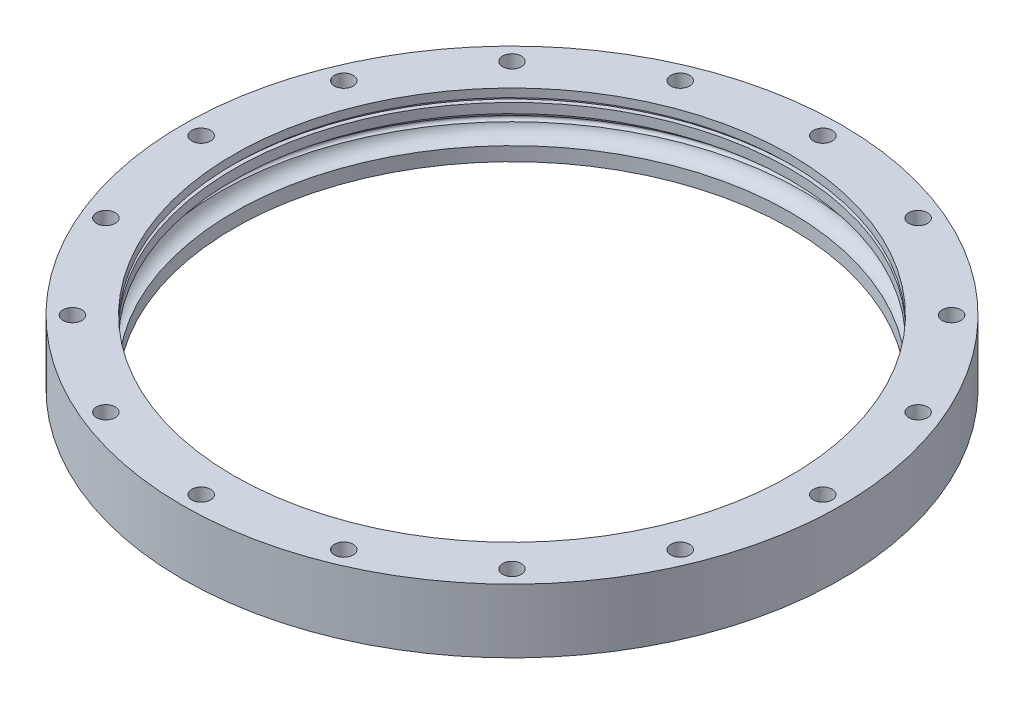
SolidWorks part; units mm, degrees
ref_plane "Plan de face" through (0, 0, 0) normal (0, 0, 1) x (1, 0, 0)
ref_plane "Plan de dessus" through (0, 0, 0) normal (0, 1, 0) x (1, 0, 0)
ref_plane "Plan de droite" through (0, 0, 0) normal (1, 0, 0) x (0, 0, -1)
sketch "Esquisse1" plane through (0, 0, 0) normal (0, 0, 1) x (1, 0, 0)
  line L0 (0, 0) -> (-237.5, 0) construction
  line L1 (-237.5, 0) -> (-237.5, 46)
  line L2 (-237.5, 46) -> (0, 46) construction
  line L3 (0, 46) -> (0, 0) construction
  line L4 (-237.5, 0) -> (-200.5, 0)
  line L5 (-200.5, 0) -> (-200.5, 10)
  line L6 (-200.5, 10) -> (-200.5, 30) construction
  line L7 (-200.5, 46) -> (-200.5, 40)
  line L8 (-200.5, 46) -> (-237.5, 46)
  line L9 (-200.5, 20) -> (-210, 20) construction
  line L10 (-210, 20) -> (-212, 20) construction
  line L11 (-200.5, 40) -> (-203.5, 40)
  line L12 (-203.5, 40) -> (-203.5, 37)
  line L13 (-203.5, 37) -> (-200.5, 37)
  line L14 (-200.5, 37) -> (-200.5, 30)
  line L15 (-200.5, 40) -> (-200.5, 37) construction
  arc A0 (-200.5, 30) -> (-200.5, 10) centre (-200.5, 20) ccw construction
  arc A1 (-210.3026, 21.977) -> (-210.3026, 18.023) centre (-210, 20) ccw
  arc A2 (-210.3026, 18.023) -> (-200.5, 10) centre (-200.5, 20) ccw
  arc A3 (-200.5, 30) -> (-210.3026, 21.977) centre (-200.5, 20) ccw
  dimension "D1" = 200.5
  dimension "D7" = 10
  dimension "D8" = 9.5
  dimension "D9" = 2
  dimension "D2" = 46
  dimension "D3" = 20
  dimension "D4" = 9
  dimension "D5" = 3
  dimension "D6" = 3
  dimension "D10" = 237.5
revolve "Révolution1" add sketch "Esquisse1" angle 360 about L3
sketch "Esquisse2" plane through (0, 46, 0) normal (0, 1, 0) x (1, 0, 0)
  line L0 (0, 0) -> (-237.5, 0) construction
  line L2 (-206.949, 85.7211) -> (0, 0) construction
  circle A0 centre (0, 0) radius 237.5 construction
  circle A1 centre (-224, 0) radius 6.75
  circle A2 centre (-206.949, 85.7211) radius 6.75
  circle A3 centre (-158.3919, 158.3919) radius 6.75
  circle A4 centre (-85.7211, 206.949) radius 6.75
  circle A5 centre (0, 224) radius 6.75
  circle A6 centre (85.7211, 206.949) radius 6.75
  circle A7 centre (158.3919, 158.3919) radius 6.75
  circle A8 centre (206.949, 85.7211) radius 6.75
  circle A9 centre (224, 0) radius 6.75
  circle A10 centre (206.949, -85.7211) radius 6.75
  circle A11 centre (158.3919, -158.3919) radius 6.75
  circle A12 centre (85.7211, -206.949) radius 6.75
  circle A13 centre (0, -224) radius 6.75
  circle A14 centre (-85.7211, -206.949) radius 6.75
  circle A15 centre (-158.3919, -158.3919) radius 6.75
  circle A16 centre (-206.949, -85.7211) radius 6.75
  point P40 (0, 0)
  dimension "D1" = 13.5
  dimension "D4" = 22.5
  dimension "D2" = 224
  dimension "D5" = 224
  dimension "D3" = 16
extrude "Enlèv. mat.-Extru.1" cut sketch "Esquisse2" against normal through all
